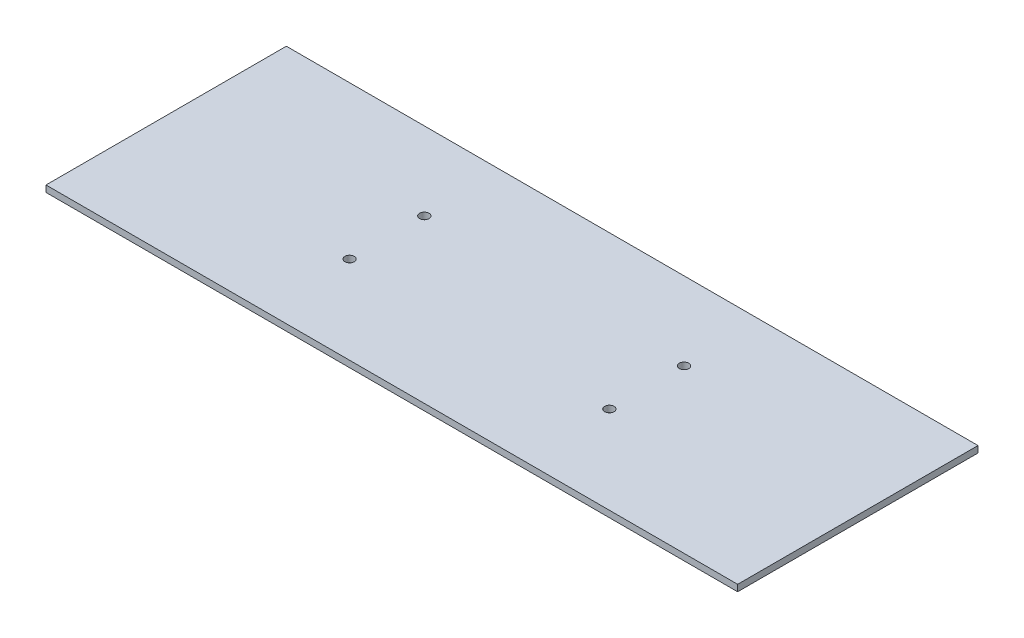
SolidWorks part; units mm, degrees
ref_plane "Front Plane" through (0, 0, 0) normal (0, 0, 1) x (1, 0, 0)
ref_plane "Top Plane" through (0, 0, 0) normal (0, 1, 0) x (1, 0, 0)
ref_plane "Right Plane" through (0, 0, 0) normal (1, 0, 0) x (0, 0, -1)
sketch "Sketch1" plane through (0, 0, 0) normal (0, 1, 0) x (1, 0, 0)
  line L0 (0, 0) -> (-40, 0) construction
  line L1 (-106.505, -38.4958) -> (106.505, -38.4958)
  line L2 (-106.505, -38.4958) -> (-106.505, 35.5242)
  line L3 (-106.505, 35.5242) -> (106.505, 35.5242)
  line L4 (106.505, -38.4958) -> (106.505, 35.5242)
  line L6 (0, 0) -> (0, 13.1387) construction
  circle A0 centre (-40, 11.5) radius 1.45
  circle A1 centre (-40, -11.5) radius 1.45
  circle A2 centre (40, -11.5) radius 1.45
  circle A3 centre (40, 11.5) radius 1.45
  point P0 (0, 0)
  point P11 (-40, 0)
  dimension "D5" = 2.9
  dimension "D6" = 2.9
  dimension "D1" = 213.01
  dimension "D2" = 74.02
  dimension "D3" = 40
  dimension "D4" = 23
extrude "Boss-Extrude1" add sketch "Sketch1" along normal blind 2
